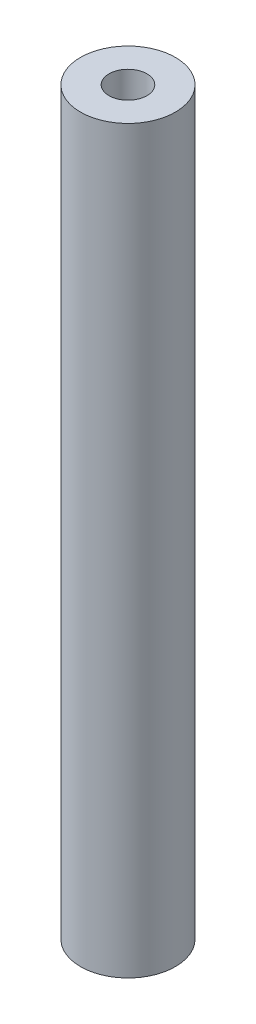
SolidWorks part; units mm, degrees
ref_plane "Front Plane" through (0, 0, 0) normal (0, 0, 1) x (1, 0, 0)
ref_plane "Top Plane" through (0, 0, 0) normal (0, 1, 0) x (1, 0, 0)
ref_plane "Right Plane" through (0, 0, 0) normal (1, 0, 0) x (0, 0, -1)
sketch "Sketch1" plane through (0, 0, 0) normal (0, 1, 0) x (1, 0, 0)
  circle A0 centre (0, 0) radius 2.5
  circle A1 centre (0, 0) radius 1
  dimension "D1" = 5
  dimension "D2" = 2
extrude "Boss-Extrude1" add sketch "Sketch1" along normal blind 39
